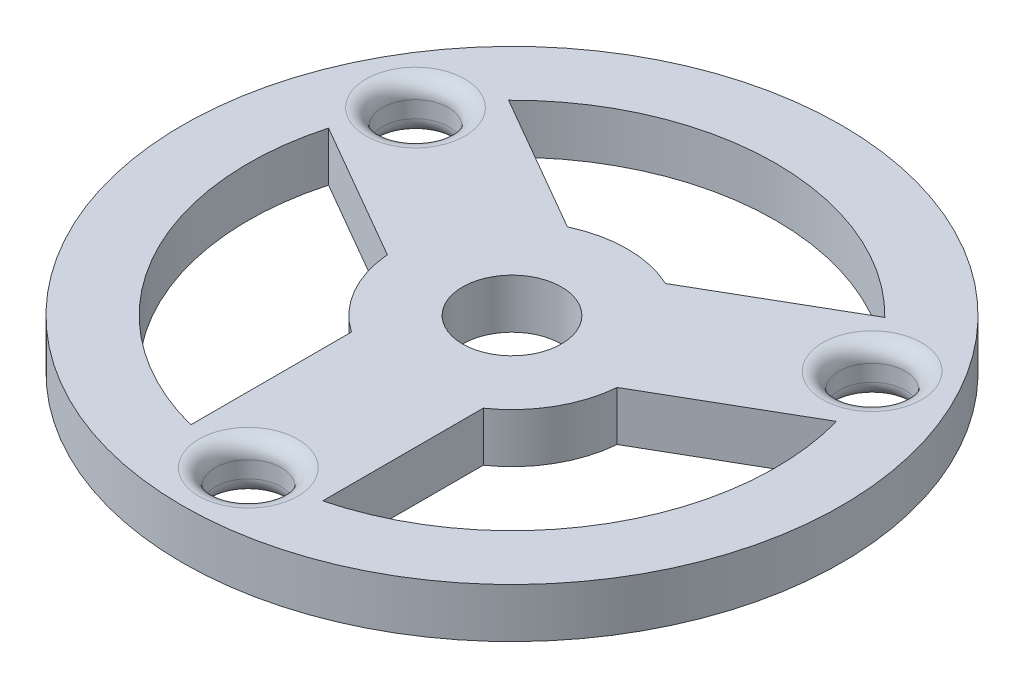
SolidWorks part; units mm, degrees
ref_plane "Front Plane" through (0, 0, 0) normal (0, 0, 1) x (1, 0, 0)
ref_plane "Top Plane" through (0, 0, 0) normal (0, 1, 0) x (1, 0, 0)
ref_plane "Right Plane" through (0, 0, 0) normal (1, 0, 0) x (0, 0, -1)
sketch "Sketch1" plane through (0, 0, 0) normal (0, 1, 0) x (1, 0, 0)
  line L0 (-6.9282, 4) -> (0, 0) construction
  line L1 (0, 0) -> (6.9282, 4) construction
  line L2 (0, 0) -> (0, -8) construction
  line L3 (0, 0) -> (0, 10) construction
  line L4 (-5.7082, 5.605) -> (-1.4875, 3.1682)
  line L5 (1.4875, 3.1682) -> (5.7082, 5.605)
  line L6 (2, -2.8723) -> (2, -7.746)
  line L7 (7.7082, 2.1409) -> (3.4875, -0.2959)
  line L8 (-3.4875, -0.2959) -> (-7.7082, 2.1409)
  line L9 (-2, -7.746) -> (-2, -2.8723)
  circle A0 centre (0, 0) radius 10
  circle A1 centre (0, 0) radius 1.5
  circle A2 centre (-6.9282, 4) radius 1
  circle A3 centre (6.9282, 4) radius 1
  circle A4 centre (0, -8) radius 1
  arc A5 (-5.7082, 5.605) -> (5.7082, 5.605) centre (0, 0) cw
  arc A6 (-1.4875, 3.1682) -> (1.4875, 3.1682) centre (0, 0) cw
  arc A7 (3.4875, -0.2959) -> (2, -2.8723) centre (0, 0) cw
  arc A8 (7.7082, 2.1409) -> (2, -7.746) centre (0, 0) cw
  arc A9 (-2, -2.8723) -> (-3.4875, -0.2959) centre (0, 0) cw
  arc A10 (-2, -7.746) -> (-7.7082, 2.1409) centre (0, 0) cw
  point P26 (0, 0)
  dimension "D1" = 10
  dimension "D5" = 2
  dimension "D8" = 2
  dimension "D7" = 2
  dimension "D9" = 3
  dimension "D2" = 8
  dimension "D3" = 120
  dimension "D4" = 120
  dimension "D6" = 2
  dimension "D10" = 3
extrude "Boss-Extrude1" add sketch "Sketch1" along normal blind 1.5
fillet "Fillet1" radius 0.5 6 edges at (0, 1.5, 9) (-6.9282, 0, -3) (6.9282, 0, -3) (0, 0, 9) (6.9282, 1.5, -3) (-6.9282, 1.5, -3)
equation "\"R_outer\"=10"
equation "\"R_inner\"=3"
